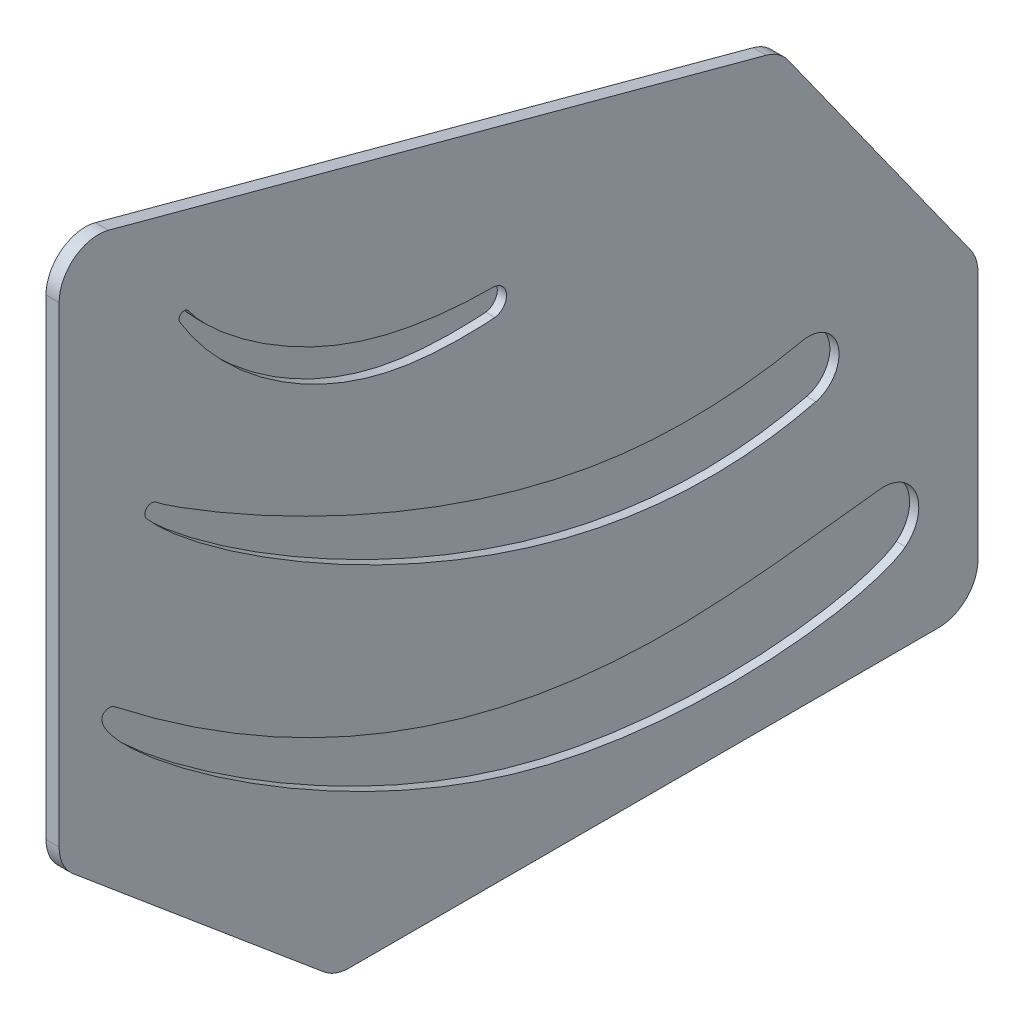
SolidWorks part; units mm, degrees
ref_plane "Front Plane" through (0, 0, 0) normal (0, 0, 1) x (1, 0, 0)
ref_plane "Top Plane" through (0, 0, 0) normal (0, 1, 0) x (1, 0, 0)
ref_plane "Right Plane" through (0, 0, 0) normal (1, 0, 0) x (0, 0, -1)
sketch "Sketch1" plane through (0, 0, 0) normal (1, 0, 0) x (0, 0, -1)
  line L0 (0, -39.1591) -> (0, -399.1591)
  line L1 (0, 303.9402) -> (0, -303.9402) construction
  line L2 (10.7164, -422.1404) -> (202.2275, -582.8373)
  line L3 (221.5111, -589.856) -> (671.5111, -589.856)
  line L4 (701.5111, -559.856) -> (701.5111, -369.856)
  line L5 (695.9285, -352.4263) -> (556.4912, -157.0875)
  line L6 (539.883, -145.5513) -> (37.8091, -10.1933)
  arc A0 (539.883, -145.5513) -> (556.4912, -157.0875) centre (532.0739, -174.5171) cw
  arc A1 (695.9285, -352.4263) -> (701.5111, -369.856) centre (671.5111, -369.856) cw
  arc A2 (701.5111, -559.856) -> (671.5111, -589.856) centre (671.5111, -559.856) cw
  arc A3 (221.5111, -589.856) -> (202.2275, -582.8373) centre (221.5111, -559.856) cw
  arc A4 (10.7164, -422.1404) -> (0, -399.1591) centre (30, -399.1591) cw
  arc A5 (0, -39.1591) -> (37.8091, -10.1933) centre (30, -39.1591) cw
  point P13 (550.2519, -148.3468)
  point P16 (701.5111, -360.2471)
  point P19 (701.5111, -589.856)
  point P22 (210.592, -589.856)
  point P25 (0, -413.1483)
  point P28 (0, 0)
  dimension "D8" = 30
  dimension "D7" = 520
  dimension "D1" = 360
  dimension "D2" = 250
  dimension "D3" = 450
  dimension "D4" = 190
  dimension "D5" = 240
  dimension "D6" = 130
extrude "Boss-Extrude1" add sketch "Sketch1" along normal blind 10
sketch "Sketch2" plane through (10, 0, 0) normal (1, 0, 0) x (0, 0, -1)
  arc A0 (626.3644, -475.9479) -> (646.1337, -523.6267) centre (629.4918, -502.5891) cw
  arc A1 (34.2074, -327.5609) -> (42.3962, -327.5609) centre (38.3018, -332.8216) cw
  arc A2 (66.6989, -215.359) -> (74.2028, -208.2845) centre (70.635, -212.0171) cw
  arc A3 (567.085, -348.1751) -> (577.7555, -393.5269) centre (572.1224, -370.9211) cw
  arc A4 (92.1634, -98.1982) -> (98.8291, -93.9889) centre (95.5389, -96.1611) cw
  arc A5 (331.1797, -194.6855) -> (332.6935, -215.359) centre (331.1807, -205.0776) cw
  spline S0 degree 3 poles (42.3962, -327.5609) (179.9982, -434.6573) (369.4962, -510.0675) (572.4274, -482.2794) (626.3644, -475.9479) knots 0 0 0 0 0.742689 1 1 1 1
  spline S1 degree 3 poles (646.1337, -523.6267) (620.2652, -544.0901) (324.8088, -589.0156) (14.4757, -342.9182) (34.2074, -327.5609) knots 0 0 0 0 0.454281 1 1 1 1
  spline S2 degree 3 poles (66.6989, -215.359) (100.32, -254.9574) (300.3222, -390.0351) (509.6397, -410.5005) (577.7555, -393.5269) knots 0 0 0 0 0.65471 1 1 1 1
  spline S3 degree 3 poles (74.2028, -208.2845) (81.1492, -214.9242) (316.0764, -369.7909) (526.7425, -357.1095) (567.085, -348.1751) knots 0 0 0 0 0.768435 1 1 1 1
  spline S4 degree 3 poles (92.1634, -98.1982) (126.325, -154.8026) (226.9187, -224.5621) (331.9217, -215.4726) (332.6935, -215.359) knots 0 0 0 0 0.645739 1 1 1 1
  spline S5 degree 3 poles (98.8291, -93.9889) (112.6228, -114.8829) (192.7302, -182.1378) (300.1844, -194.6883) (331.1797, -194.6855) knots 0 0 0 0 0.660883 1 1 1 1
  point P20 (0, 0)
  point P22 (248.2679, -175.7269)
  point P23 (98.8291, -93.9889)
  point P24 (243.0715, -179.9398)
  point P27 (330.6114, -186.9064)
  point P29 (0, 0)
  point P30 (230.4501, -179.8851)
  point P31 (0, 0)
  point P32 (331.1807, -194.6855)
  point P33 (255.1755, -205.0776)
  point P34 (92.1634, -98.1982)
  point P35 (74.2028, -208.2845)
  point P36 (258.0782, -212.0171)
  point P37 (0, 0)
  point P38 (0, 0)
  point P39 (29.3498, -331.8519)
  point P40 (34.2074, -327.5609)
  point P41 (0, 0)
sketch "Sketch4" plane through (10, 0, 0) normal (1, 0, 0) x (0, 0, -1)
  arc A2 (646.1337, -523.6267) -> (626.3644, -475.9479) centre (629.4918, -502.5891) ccw
  arc A3 (42.3962, -327.5609) -> (34.2074, -327.5609) centre (38.3018, -332.8216) ccw
  arc A4 (646.1337, -523.6267) -> (626.3644, -475.9479) centre (629.4918, -502.5891) ccw
  arc A5 (42.3962, -327.5609) -> (34.2074, -327.5609) centre (38.3018, -332.8216) ccw
  arc A6 (332.6935, -215.359) -> (331.1797, -194.6855) centre (331.1807, -205.0776) ccw
  arc A7 (98.8291, -93.9889) -> (92.1634, -98.1982) centre (95.5389, -96.1611) ccw
  arc A8 (332.6935, -215.359) -> (331.1797, -194.6855) centre (331.1807, -205.0776) ccw
  arc A9 (98.8291, -93.9889) -> (92.1634, -98.1982) centre (95.5389, -96.1611) ccw
  arc A10 (74.2028, -208.2845) -> (66.6989, -215.359) centre (70.635, -212.0171) ccw
  arc A11 (577.7555, -393.5269) -> (567.085, -348.1751) centre (572.1224, -370.9211) ccw
  arc A12 (74.2028, -208.2845) -> (66.6989, -215.359) centre (70.635, -212.0171) ccw
  arc A13 (577.7555, -393.5269) -> (567.085, -348.1751) centre (572.1224, -370.9211) ccw
  spline S2 degree 3 poles (2464.2398, -2081.6505) (-548.195, 323.3051) (405.5921, -1163.7485) (1230.0919, -121.6341) (-2282.2479, -1142.4189) knots -0.887673 -0.887673 -0.887673 -0.887673 0.545719 2.060312 2.060312 2.060312 2.060312 only from (34.2074, -327.5609) to (646.1337, -523.6267)
  spline S3 degree 3 poles (2226.5612, -2865.6665) (1323.6455, -69.1428) (133.2418, -1164.4427) (-685.8944, 592.4388) (-1408.6195, 2279.9581) knots -1.749601 -1.749601 -1.749601 -1.749601 0.257311 3.507574 3.507574 3.507574 3.507574 only from (626.3644, -475.9479) to (42.3962, -327.5609)
  spline S4 degree 3 poles (34.2074, -327.5609) (14.4757, -342.9182) (324.8088, -589.0156) (620.2652, -544.0901) (646.1337, -523.6267) knots 0 0 0 0 0.545719 1 1 1 1
  spline S5 degree 3 poles (626.3644, -475.9479) (572.4274, -482.2794) (369.4962, -510.0675) (179.9982, -434.6573) (42.3962, -327.5609) knots 0 0 0 0 0.257311 1 1 1 1
  spline S6 degree 3 poles (3002.0956, -225.384) (-363.2568, 729.6054) (66.8164, -586.9794) (599.3431, -71.4658) (-2590.2798, -887.555) knots -2.579265 -2.579265 -2.579265 -2.579265 0.645739 2.241059 2.241059 2.241059 2.241059 only from (92.1634, -98.1982) to (332.6935, -215.359)
  spline S7 degree 3 poles (-2662.3277, -256.9179) (955.8415, 48.1602) (11.379, -589.6416) (-105.524, 428.0104) (2149.1755, -2277.9565) knots -2.348836 -2.348836 -2.348836 -2.348836 0.339117 3.152231 3.152231 3.152231 3.152231 only from (331.1797, -194.6855) to (98.8291, -93.9889)
  spline S8 degree 3 poles (92.1634, -98.1982) (126.325, -154.8026) (226.9187, -224.5621) (331.9217, -215.4726) (332.6935, -215.359) knots 0 0 0 0 0.645739 1 1 1 1
  spline S9 degree 3 poles (331.1797, -194.6855) (300.1844, -194.6883) (192.7302, -182.1378) (112.6228, -114.8829) (98.8291, -93.9889) knots 0 0 0 0 0.339117 1 1 1 1
  spline S10 degree 3 poles (-2402.1254, -319.3194) (1153.6868, 137.1649) (482.2001, -995.3544) (-564.3045, 462.0117) (2387.365, -2117.1897) knots -1.643548 -1.643548 -1.643548 -1.643548 0.231565 2.288063 2.288063 2.288063 2.288063 only from (567.085, -348.1751) to (74.2028, -208.2845)
  spline S11 degree 3 poles (2529.9268, -1920.9073) (-482.2509, 413.9802) (286.5344, -859.8048) (1214.5614, -174.3342) (713.7018, 2525.3071) knots -1.509473 -1.509473 -1.509473 -1.509473 0.65471 2.625093 2.625093 2.625093 2.625093 only from (66.6989, -215.359) to (577.7555, -393.5269)
  spline S12 degree 3 poles (567.085, -348.1751) (526.7425, -357.1095) (316.0764, -369.7909) (81.1492, -214.9242) (74.2028, -208.2845) knots 0 0 0 0 0.231565 1 1 1 1
  spline S13 degree 3 poles (66.6989, -215.359) (100.32, -254.9574) (300.3222, -390.0351) (509.6397, -410.5005) (577.7555, -393.5269) knots 0 0 0 0 0.65471 1 1 1 1
  dimension "D1" = 0
  dimension "D2" = 0
  dimension "D3" = 0
extrude "Cut-Extrude2" cut sketch "Sketch4" against normal blind 7
